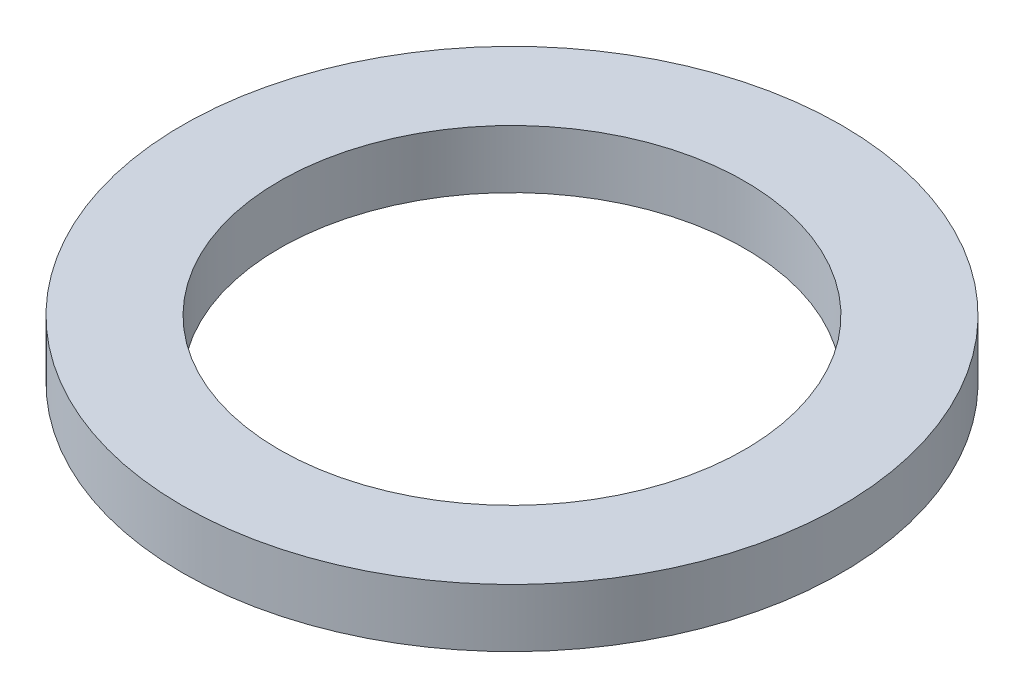
SolidWorks part; units mm, degrees
ref_plane "Front Plane" through (0, 0, 0) normal (0, 0, 1) x (1, 0, 0)
ref_plane "Top Plane" through (0, 0, 0) normal (0, 1, 0) x (1, 0, 0)
ref_plane "Right Plane" through (0, 0, 0) normal (1, 0, 0) x (0, 0, -1)
sketch "Sketch1" plane through (0, 0, 0) normal (0, 1, 0) x (1, 0, 0)
  circle A0 centre (0, 0) radius 6
  circle A1 centre (0, 0) radius 8.5
  dimension "D1" = 12
  dimension "D2" = 17
extrude "Boss-Extrude1" add sketch "Sketch1" along normal blind 1.5
